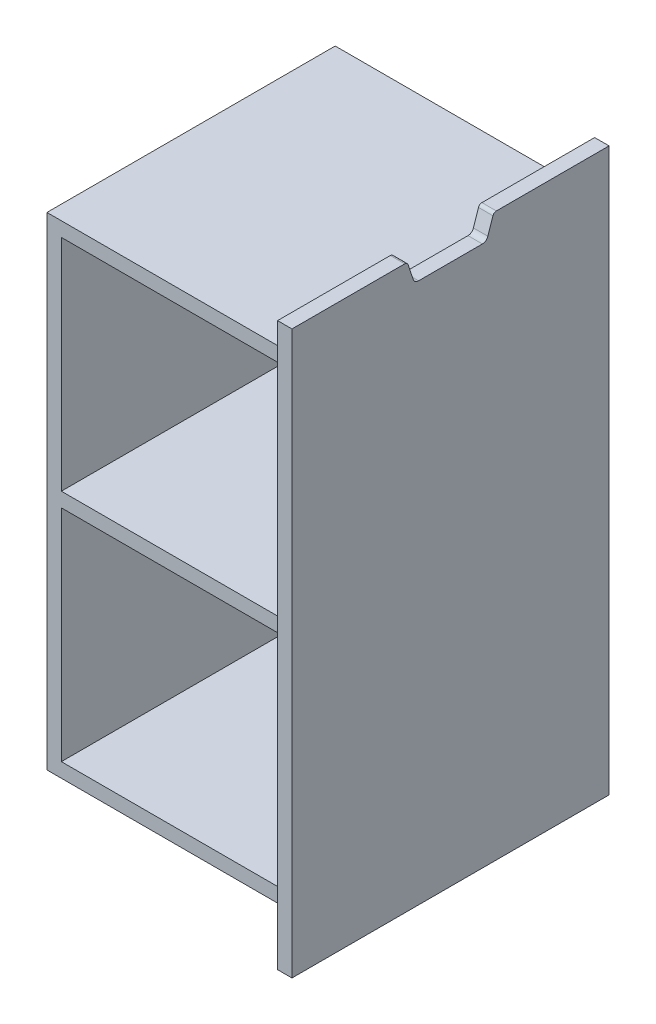
SolidWorks part; units mm, degrees
ref_plane "Front Plane" through (0, 0, 0) normal (0, 0, 1) x (1, 0, 0)
ref_plane "Top Plane" through (0, 0, 0) normal (0, 1, 0) x (1, 0, 0)
ref_plane "Right Plane" through (0, 0, 0) normal (1, 0, 0) x (0, 0, -1)
sketch "Sketch1" plane through (0, 0, 0) normal (0, 1, 0) x (1, 0, 0)
  line L1 (-170, 200) -> (170, 200)
  line L2 (-170, 200) -> (-170, -200)
  line L3 (-170, -200) -> (170, -200)
  line L4 (170, 200) -> (170, -200)
  line L5 (-170, 200) -> (170, -200) construction
  line L6 (-170, -200) -> (170, 200) construction
  point P0 (0, 0)
  dimension "D1" = 340
  dimension "D2" = 400
extrude "Boss-Extrude1" add sketch "Sketch1" along normal blind 20
sketch "Sketch2" plane through (0, 20, 0) normal (0, 1, 0) x (1, 0, 0)
  line L0 (-170, -200) -> (170, -200) construction
  line L1 (-170, 200) -> (-150, 200)
  line L2 (-170, 200) -> (-170, -200)
  line L3 (-170, -200) -> (-150, -200)
  line L4 (-150, 200) -> (-150, -200)
  dimension "D1" = 20
extrude "Boss-Extrude2" add sketch "Sketch2" along normal blind 630
ref_plane "Plane1" through (0, 335, 0) normal (0, 1, 0) x (1, 0, 0)
sketch "Sketch3" plane through (0, 335, 0) normal (0, 1, 0) x (1, 0, 0)
  line L0 (-150, -200) -> (170, -200) construction
  line L1 (-150, 200) -> (150, 200)
  line L2 (-150, 200) -> (-150, -200)
  line L3 (-150, -200) -> (150, -200)
  line L4 (150, 200) -> (150, -200)
  dimension "D1" = 300
extrude "Boss-Extrude3" add sketch "Sketch3" along normal mid plane 20
mirror "Mirror1" about plane through (0, 335, 0) normal (0, 1, 0) of "Boss-Extrude1"
mirror "Mirror2" about plane through (0, 0, 0) normal (1, 0, 0) of "Boss-Extrude2"
sketch "Sketch8" plane through (0, 0, 200) normal (0, 0, 1) x (1, 0, 0)
  line L0 (-170, 0) -> (170, 0) construction
  line L1 (170, -60) -> (190, -60)
  line L2 (170, -60) -> (170, 720)
  line L3 (170, 720) -> (190, 720)
  line L4 (190, -60) -> (190, 720)
  dimension "D1" = 20
  dimension "D2" = 60
  dimension "D3" = 780
extrude "Boss-Extrude4" add sketch "Sketch8" against normal blind 420 and the other way blind 20
sketch "Sketch9" plane through (190, 0, 0) normal (1, 0, 0) x (0, 0, -1)
  line L0 (-60, 720) -> (-51.8234, 695.4702)
  line L1 (-220, 720) -> (220, 720) construction
  line L2 (-44.2339, 690) -> (44.2339, 690)
  line L3 (51.8234, 695.4702) -> (60, 720)
  line L4 (-60, 720) -> (60, 720)
  arc A0 (44.2339, 690) -> (51.8234, 695.4702) centre (44.2339, 698) ccw
  arc A1 (-51.8234, 695.4702) -> (-44.2339, 690) centre (-44.2339, 698) ccw
  point P10 (50, 690)
  point P13 (-50, 690)
  dimension "D6" = 8
  dimension "D1" = 160
  dimension "D2" = 160
  dimension "D3" = 100
  dimension "D4" = 10
  dimension "D5" = 30
extrude "Cut-Extrude4" cut sketch "Sketch9" against normal up to surface (20 mm away) up to face at (170, 330, 0)
fillet "Fillet1" radius 5 2 edges at (180, 720, 60) (180, 720, -60)
sketch "Sketch10" plane through (-170, 0, 0) normal (-1, 0, 0) x (0, 0, 1)
  line L0 (200, 670) -> (-200, 670) construction
  circle A0 centre (174, 628.5) radius 3
  circle A1 centre (142.5, 628.5) radius 3
  circle A2 centre (111, 628.5) radius 3
  dimension "D4" = 6
  dimension "D3" = 41.5
  dimension "D1" = 41.5
  dimension "D2" = 41.5
extrude "Cut-Extrude5" cut sketch "Sketch10" against normal blind 13
mirror "Mirror3" about plane through (0, 0, 0) normal (0, 0, 1) of "Cut-Extrude5"
sketch "Sketch11" plane through (0, 0, 0) normal (0, -1, 0) x (1, 0, 0)
  line L0 (-170, -200) -> (-170, 200) construction
  line L2 (-130, -140) -> (-130, -160)
  line L4 (-70, -140) -> (-70, -160)
  line L6 (-130, -140) -> (-121, -140) construction
  line L7 (-79, -140) -> (-70, -140) construction
  circle A0 centre (-124, -140) radius 3
  circle A1 centre (-76, -140) radius 3
  dimension "D6" = 6
  dimension "D7" = 6
  dimension "D1" = 40
  dimension "D5" = 6
extrude "Cut-Extrude6" cut sketch "Sketch11" against normal blind 13 contours A0 | A1
mirror "Mirror4" about plane through (0, 0, 0) normal (1, 0, 0) of "Cut-Extrude6"
mirror "Mirror5" about plane through (0, 0, 0) normal (0, 0, 1) of "Mirror4", "Cut-Extrude6"
